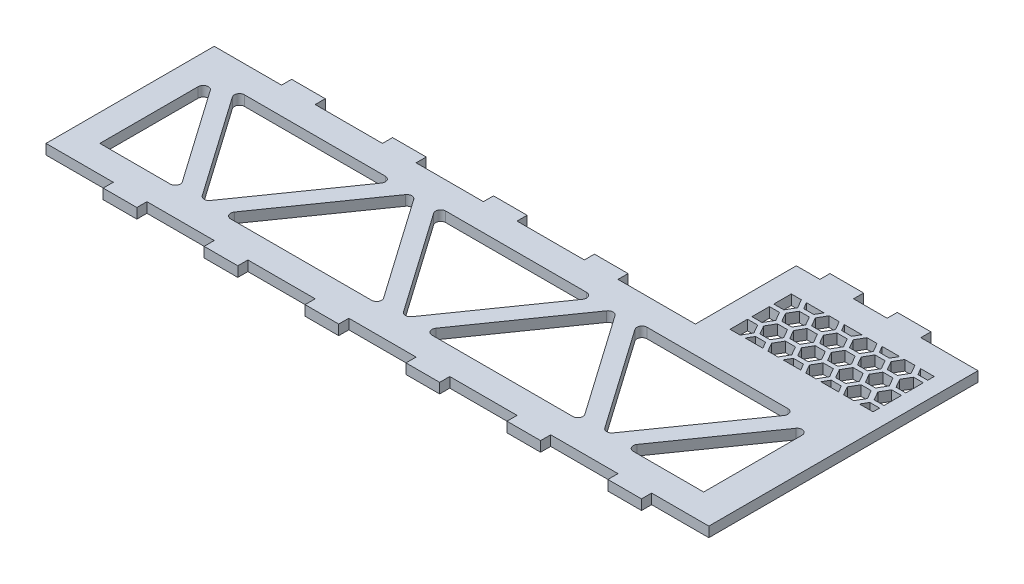
SolidWorks part; units mm, degrees
ref_plane "Front Plane" through (0, 0, 0) normal (0, 0, 1) x (1, 0, 0)
ref_plane "Top Plane" through (0, 0, 0) normal (0, 1, 0) x (1, 0, 0)
ref_plane "Right Plane" through (0, 0, 0) normal (1, 0, 0) x (0, 0, -1)
sketch "Sketch1" plane through (0, 0, 0) normal (0, 1, 0) x (1, 0, 0)
  line L0 (-71.5, -25) -> (125.5, -25)
  line L1 (-71.5, 25) -> (71.5, 25)
  line L2 (-71.5, 25) -> (-71.5, -25)
  line L8 (71.5, 25) -> (71.5, 55)
  line L9 (71.5, 55) -> (125.5, 55)
  line L10 (125.5, -25) -> (125.5, 55)
  point P0 (0, 0)
  dimension "D1" = 143
  dimension "D2" = 50
  dimension "D3" = 54
  dimension "D4" = 80
extrude "Boss-Extrude1" add sketch "Sketch1" along normal blind 3
sketch "Sketch6" plane through (0, 3, 0) normal (0, 1, 0) x (1, 0, 0)
  line L0 (-63.5, 12.2426) -> (-63.5, -17)
  line L1 (-63.5, -17) -> (-42.5744, -17)
  line L2 (-41.3457, -14.6396) -> (-60.7713, 13.103)
  line L3 (71.5, 25) -> (-71.5, 25) construction
  line L4 (-71.5, -25) -> (125.5, -25) construction
  line L5 (-71.5, 25) -> (-71.5, -25) construction
  line L6 (-55.7434, 14.6396) -> (-34.8178, -15.2452)
  line L7 (-32.3603, -15.2452) -> (-11.4348, 14.6396)
  line L8 (-12.6635, 17) -> (-54.5147, 17)
  line L9 (-4.9069, 15.2452) -> (-25.8325, -14.6396)
  line L10 (-2.4494, 15.2452) -> (18.4762, -14.6396)
  line L11 (17.2474, -17) -> (-24.6037, -17)
  line L12 (47.1584, 17) -> (5.3072, 17)
  line L13 (4.0785, 14.6396) -> (25.0041, -15.2452)
  line L14 (27.4615, -15.2452) -> (48.3871, 14.6396)
  line L15 (33.9894, -14.6396) -> (54.915, 15.2452)
  line L17 (77.0693, -17) -> (35.2181, -17)
  line L18 (78.298, -14.6396) -> (57.3724, 15.2452)
  line L19 (106.9802, 17) -> (65.1291, 17)
  line L20 (63.9003, 14.6396) -> (84.8259, -15.2452)
  line L21 (87.2834, -15.2452) -> (108.209, 14.6396)
  line L24 (95.04, -17) -> (115.9656, -17)
  line L25 (93.8113, -14.6396) -> (113.2368, 13.103)
  line L26 (115.9656, 12.2426) -> (115.9656, -17)
  arc A0 (95.04, -17) -> (93.8113, -14.6396) centre (95.04, -15.5) cw
  arc A1 (115.9656, 12.2426) -> (113.2368, 13.103) centre (114.4656, 12.2426) ccw
  arc A2 (77.0693, -17) -> (78.298, -14.6396) centre (77.0693, -15.5) ccw
  arc A3 (33.9894, -14.6396) -> (35.2181, -17) centre (35.2181, -15.5) ccw
  arc A4 (54.915, 15.2452) -> (57.3724, 15.2452) centre (56.1437, 14.3848) cw
  arc A5 (47.1584, 17) -> (48.3871, 14.6396) centre (47.1584, 15.5) cw
  arc A6 (25.0041, -15.2452) -> (27.4615, -15.2452) centre (26.2328, -14.3848) ccw
  arc A7 (5.3072, 17) -> (4.0785, 14.6396) centre (5.3072, 15.5) ccw
  arc A8 (18.4762, -14.6396) -> (17.2474, -17) centre (17.2474, -15.5) cw
  arc A9 (-4.9069, 15.2452) -> (-2.4494, 15.2452) centre (-3.6781, 14.3848) cw
  arc A10 (-25.8325, -14.6396) -> (-24.6037, -17) centre (-24.6037, -15.5) ccw
  arc A11 (-34.8178, -15.2452) -> (-32.3603, -15.2452) centre (-33.5891, -14.3848) ccw
  arc A12 (-11.4348, 14.6396) -> (-12.6635, 17) centre (-12.6635, 15.5) ccw
  arc A13 (-55.7434, 14.6396) -> (-54.5147, 17) centre (-54.5147, 15.5) cw
  arc A14 (-42.5744, -17) -> (-41.3457, -14.6396) centre (-42.5744, -15.5) ccw
  arc A15 (-63.5, 12.2426) -> (-60.7713, 13.103) centre (-62, 12.2426) cw
  arc A16 (87.2834, -15.2452) -> (84.8259, -15.2452) centre (86.0546, -14.3848) cw
  arc A17 (106.9802, 17) -> (108.209, 14.6396) centre (106.9802, 15.5) cw
  arc A18 (65.1291, 17) -> (63.9003, 14.6396) centre (65.1291, 15.5) ccw
  point P31 (92.1585, -17)
  point P34 (115.9656, 17)
  point P37 (79.9508, -17)
  point P40 (32.3367, -17)
  point P43 (56.1437, 17)
  point P46 (50.0398, 17)
  point P55 (-3.6781, 17)
  point P58 (-27.4852, -17)
  point P61 (-33.5891, -17)
  point P68 (-39.6929, -17)
  point P71 (-63.5, 17)
  dimension "D17" = 1.5
  dimension "D18" = 1.5
  dimension "D1" = 8
  dimension "D2" = 8
  dimension "D3" = 8
  dimension "D4" = 55
  dimension "D5" = 5
  dimension "D6" = 55
  dimension "D7" = 8
  dimension "D8" = 5
  dimension "D9" = 8
  dimension "D10" = 8
  dimension "D12" = 5
  dimension "D13" = 5
  dimension "D14" = 8
  dimension "D16" = 5
  dimension "D11" = 2
  dimension "D15" = 2
extrude "Cut-Extrude5" cut sketch "Sketch6" against normal blind 10
sketch "Sketch7" plane through (0, 3, 0) normal (0, 1, 0) x (1, 0, 0)
  line L0 (125.5, 55) -> (71.5, 55) construction
  line L1 (78, 47) -> (81, 47)
  line L4 (120.5, 47) -> (120.5, 45.0558)
  line L5 (89.2494, 28.8038) -> (92.2494, 28.8038)
  line L6 (100.4967, 28.8038) -> (103.4967, 28.8038)
  line L7 (104.9956, 28.8038) -> (110.245, 28.8038)
  line L9 (78, 47) -> (81, 47)
  line L10 (81, 47) -> (82.5, 44.4019)
  line L11 (82.5, 44.4019) -> (81, 41.8038)
  line L12 (81, 41.8038) -> (78, 41.8038)
  line L16 (78, 40.5) -> (81, 40.5)
  line L17 (81, 40.5) -> (82.5, 37.9019)
  line L18 (82.5, 37.9019) -> (81, 35.3038)
  line L19 (81, 35.3038) -> (78, 35.3038)
  line L22 (78, 34) -> (81, 34)
  line L23 (81, 34) -> (82.5, 31.4019)
  line L24 (82.5, 31.4019) -> (81, 28.8038)
  line L25 (81, 28.8038) -> (78, 28.8038)
  line L68 (82.1258, 41.1538) -> (83.6258, 43.7519)
  line L69 (82.1258, 41.1538) -> (83.6258, 38.5558)
  line L70 (83.6258, 43.7519) -> (86.6258, 43.7519)
  line L71 (83.6258, 38.5558) -> (86.6258, 38.5558)
  line L72 (82.5011, 28.8038) -> (87.7506, 28.8038)
  line L73 (88.1258, 41.1538) -> (86.6258, 38.5558)
  line L74 (88.1258, 41.1538) -> (86.6258, 43.7519)
  line L75 (88.1258, 34.6538) -> (86.6258, 32.0558)
  line L76 (83.6258, 32.0558) -> (86.6258, 32.0558)
  line L77 (82.1258, 34.6538) -> (83.6258, 32.0558)
  line L78 (82.1258, 34.6538) -> (83.6258, 37.2519)
  line L79 (83.6258, 37.2519) -> (86.6258, 37.2519)
  line L80 (88.1258, 34.6538) -> (86.6258, 37.2519)
  line L84 (82.5011, 28.8038) -> (83.6258, 30.7519)
  line L85 (83.6258, 30.7519) -> (86.6258, 30.7519)
  line L86 (87.7506, 28.8038) -> (86.6258, 30.7519)
  line L129 (82.1258, -17.3462) -> (83.6258, -19.9442) [skipped]
  line L130 (83.6258, -19.9442) -> (86.6258, -19.9442) [skipped]
  line L131 (88.1258, -17.3462) -> (86.6258, -19.9442) [skipped]
  line L133 (87.7483, 47) -> (86.6258, 45.0558)
  line L134 (83.6258, 45.0558) -> (86.6258, 45.0558)
  line L135 (82.5033, 47) -> (83.6258, 45.0558)
  line L139 (83.6258, 50.2519) -> (86.6258, 50.2519) [skipped]
  line L140 (82.1258, 47.6538) -> (83.6258, 50.2519) [skipped]
  line L141 (88.1258, 47.6538) -> (86.6258, 50.2519) [skipped]
  line L142 (89.2494, 47) -> (87.7494, 44.4019)
  line L143 (87.7494, 44.4019) -> (89.2494, 41.8038)
  line L144 (89.2494, 41.8038) -> (92.2494, 41.8038)
  line L145 (89.2494, 47) -> (92.2494, 47)
  line L146 (93.7494, 44.4019) -> (92.2494, 41.8038)
  line L147 (92.2494, 47) -> (93.7494, 44.4019)
  line L148 (89.2494, 40.5) -> (92.2494, 40.5)
  line L149 (92.2494, 40.5) -> (93.7494, 37.9019)
  line L150 (93.7494, 37.9019) -> (92.2494, 35.3038)
  line L151 (89.2494, 35.3038) -> (92.2494, 35.3038)
  line L152 (87.7494, 37.9019) -> (89.2494, 35.3038)
  line L153 (89.2494, 40.5) -> (87.7494, 37.9019)
  line L154 (89.2494, 34) -> (92.2494, 34)
  line L155 (92.2494, 34) -> (93.7494, 31.4019)
  line L156 (93.7494, 31.4019) -> (92.2494, 28.8038)
  line L157 (89.2494, 28.8038) -> (92.2494, 28.8038)
  line L158 (87.7494, 31.4019) -> (89.2494, 28.8038)
  line L159 (89.2494, 34) -> (87.7494, 31.4019)
  line L202 (111.7439, 28.8038) -> (114.7439, 28.8038)
  line L203 (82.5033, 47) -> (87.7483, 47)
  line L204 (98.9956, 47) -> (97.8731, 45.0558)
  line L205 (97.8731, 45.0558) -> (94.8731, 45.0558)
  line L206 (93.7506, 47) -> (94.8731, 45.0558)
  line L207 (98.9956, 47) -> (93.7506, 47)
  line L208 (93.3731, 41.1538) -> (94.8731, 43.7519)
  line L209 (97.8731, 43.7519) -> (94.8731, 43.7519)
  line L210 (99.3731, 41.1538) -> (97.8731, 43.7519)
  line L211 (99.3731, 41.1538) -> (97.8731, 38.5558)
  line L212 (97.8731, 38.5558) -> (94.8731, 38.5558)
  line L213 (93.3731, 41.1538) -> (94.8731, 38.5558)
  line L214 (93.3731, 34.6538) -> (94.8731, 37.2519)
  line L215 (97.8731, 37.2519) -> (94.8731, 37.2519)
  line L216 (99.3731, 34.6538) -> (97.8731, 37.2519)
  line L217 (99.3731, 34.6538) -> (97.8731, 32.0558)
  line L218 (97.8731, 32.0558) -> (94.8731, 32.0558)
  line L219 (93.3731, 34.6538) -> (94.8731, 32.0558)
  line L220 (93.7483, 28.8038) -> (94.8731, 30.7519)
  line L221 (97.8731, 30.7519) -> (94.8731, 30.7519)
  line L222 (98.9978, 28.8038) -> (97.8731, 30.7519)
  line L262 (93.7483, 28.8038) -> (98.9978, 28.8038)
  line L263 (103.4967, 47) -> (104.9967, 44.4019)
  line L264 (104.9967, 44.4019) -> (103.4967, 41.8038)
  line L265 (103.4967, 41.8038) -> (100.4967, 41.8038)
  line L266 (98.9967, 44.4019) -> (100.4967, 41.8038)
  line L267 (100.4967, 47) -> (98.9967, 44.4019)
  line L268 (103.4967, 47) -> (100.4967, 47)
  line L269 (103.4967, 40.5) -> (104.9967, 37.9019)
  line L270 (104.9967, 37.9019) -> (103.4967, 35.3038)
  line L271 (103.4967, 35.3038) -> (100.4967, 35.3038)
  line L272 (98.9967, 37.9019) -> (100.4967, 35.3038)
  line L273 (100.4967, 40.5) -> (98.9967, 37.9019)
  line L274 (103.4967, 40.5) -> (100.4967, 40.5)
  line L275 (103.4967, 34) -> (104.9967, 31.4019)
  line L276 (104.9967, 31.4019) -> (103.4967, 28.8038)
  line L277 (103.4967, 28.8038) -> (100.4967, 28.8038)
  line L278 (98.9967, 31.4019) -> (100.4967, 28.8038)
  line L279 (100.4967, 34) -> (98.9967, 31.4019)
  line L280 (103.4967, 34) -> (100.4967, 34)
  line L323 (116.458, 28.8038) -> (120.5, 28.8038)
  line L324 (104.9978, 47) -> (110.2428, 47)
  line L325 (110.2428, 47) -> (109.1203, 45.0558)
  line L326 (106.1203, 45.0558) -> (109.1203, 45.0558)
  line L327 (104.9978, 47) -> (106.1203, 45.0558)
  line L328 (110.6203, 41.1538) -> (109.1203, 38.5558)
  line L329 (106.1203, 38.5558) -> (109.1203, 38.5558)
  line L330 (104.6203, 41.1538) -> (106.1203, 38.5558)
  line L331 (104.6203, 41.1538) -> (106.1203, 43.7519)
  line L332 (106.1203, 43.7519) -> (109.1203, 43.7519)
  line L333 (110.6203, 41.1538) -> (109.1203, 43.7519)
  line L334 (110.6203, 34.6538) -> (109.1203, 32.0558)
  line L335 (106.1203, 32.0558) -> (109.1203, 32.0558)
  line L336 (104.6203, 34.6538) -> (106.1203, 32.0558)
  line L337 (104.6203, 34.6538) -> (106.1203, 37.2519)
  line L338 (106.1203, 37.2519) -> (109.1203, 37.2519)
  line L339 (110.6203, 34.6538) -> (109.1203, 37.2519)
  line L343 (104.9956, 28.8038) -> (106.1203, 30.7519)
  line L344 (106.1203, 30.7519) -> (109.1203, 30.7519)
  line L345 (110.245, 28.8038) -> (109.1203, 30.7519)
  line L382 (78, 47) -> (78, 41.8038)
  line L383 (111.7439, 47) -> (114.7439, 47)
  line L384 (114.7439, 47) -> (116.2439, 44.4019)
  line L385 (116.2439, 44.4019) -> (114.7439, 41.8038)
  line L386 (111.7439, 41.8038) -> (114.7439, 41.8038)
  line L387 (110.2439, 44.4019) -> (111.7439, 41.8038)
  line L388 (111.7439, 47) -> (110.2439, 44.4019)
  line L389 (111.7439, 40.5) -> (114.7439, 40.5)
  line L390 (114.7439, 40.5) -> (116.2439, 37.9019)
  line L391 (116.2439, 37.9019) -> (114.7439, 35.3038)
  line L392 (111.7439, 35.3038) -> (114.7439, 35.3038)
  line L393 (110.2439, 37.9019) -> (111.7439, 35.3038)
  line L394 (111.7439, 40.5) -> (110.2439, 37.9019)
  line L395 (111.7439, 34) -> (114.7439, 34)
  line L396 (114.7439, 34) -> (116.2439, 31.4019)
  line L397 (116.2439, 31.4019) -> (114.7439, 28.8038)
  line L398 (111.7439, 28.8038) -> (114.7439, 28.8038)
  line L399 (110.2439, 31.4019) -> (111.7439, 28.8038)
  line L400 (111.7439, 34) -> (110.2439, 31.4019)
  line L443 (78, 34) -> (78, 28.8038)
  line L445 (120.5, 45.0558) -> (117.5827, 45.0558)
  line L446 (116.4602, 47) -> (117.5827, 45.0558)
  line L447 (120.5, 47) -> (116.4602, 47)
  line L448 (116.0827, 41.1538) -> (117.5827, 43.7519)
  line L449 (120.5, 43.7519) -> (117.5827, 43.7519)
  line L452 (120.5, 38.5558) -> (117.5827, 38.5558)
  line L453 (116.0827, 41.1538) -> (117.5827, 38.5558)
  line L454 (116.0827, 34.6538) -> (117.5827, 37.2519)
  line L455 (120.5, 37.2519) -> (117.5827, 37.2519)
  line L458 (120.5, 32.0558) -> (117.5827, 32.0558)
  line L459 (116.0827, 34.6538) -> (117.5827, 32.0558)
  line L460 (116.458, 28.8038) -> (117.5827, 30.7519)
  line L461 (120.5, 30.7519) -> (117.5827, 30.7519)
  line L502 (78, 40.5) -> (78, 35.3038)
  line L526 (120.5, 30.7519) -> (120.5, 28.8038)
  line L527 (120.5, 37.2519) -> (120.5, 32.0558)
  line L528 (120.5, 43.7519) -> (120.5, 38.5558)
  line L529 (116.4602, 47) -> (120.5, 47)
  line L530 (111.7439, 47) -> (114.7439, 47)
  line L531 (104.9978, 47) -> (110.2428, 47)
  line L532 (100.4967, 47) -> (103.4967, 47)
  line L533 (93.7506, 47) -> (98.9956, 47)
  line L534 (89.2494, 47) -> (92.2494, 47)
  line L535 (82.5033, 47) -> (87.7483, 47)
  line L536 (81, 27.5) -> (82.5, 24.9019) [skipped]
  line L537 (82.1258, 28.1538) -> (83.6258, 25.5558) [skipped]
  line L538 (88.1258, 28.1538) -> (86.6258, 25.5558) [skipped]
  line L539 (89.2494, 27.5) -> (87.7494, 24.9019) [skipped]
  line L540 (92.2494, 27.5) -> (93.7494, 24.9019) [skipped]
  line L541 (100.4967, 27.5) -> (98.9967, 24.9019) [skipped]
  line L542 (103.4967, 27.5) -> (104.9967, 24.9019) [skipped]
  line L543 (106.1203, 25.5558) -> (109.1203, 25.5558) [skipped]
  line L544 (110.2439, 24.9019) -> (111.7439, 22.3038) [skipped]
  line L545 (116.2439, 24.9019) -> (114.7439, 22.3038) [skipped]
  line L546 (114.7439, 21) -> (116.2439, 18.4019) [skipped]
  line L547 (110.2439, 18.4019) -> (111.7439, 15.8038) [skipped]
  line L548 (110.6203, 15.1538) -> (109.1203, 17.7519) [skipped]
  line L549 (104.6203, 15.1538) -> (106.1203, 12.5558) [skipped]
  line L550 (103.4967, 14.5) -> (100.4967, 14.5) [skipped]
  line L551 (100.4967, 14.5) -> (98.9967, 11.9019) [skipped]
  line L552 (99.3731, 15.1538) -> (97.8731, 12.5558) [skipped]
  line L553 (93.3731, 15.1538) -> (94.8731, 17.7519) [skipped]
  line L554 (93.7494, 18.4019) -> (92.2494, 15.8038) [skipped]
  line L555 (87.7494, 18.4019) -> (89.2494, 15.8038) [skipped]
  line L556 (83.6258, 19.0558) -> (86.6258, 19.0558) [skipped]
  line L557 (82.1258, 21.6538) -> (83.6258, 19.0558) [skipped]
  line L558 (81, 22.3038) -> (78, 22.3038) [skipped]
  line L560 (78, 27.5) -> (81, 27.5) [skipped]
  line L562 (82.1258, 21.6538) -> (83.6258, 24.2519) [skipped]
  line L563 (88.1258, 21.6538) -> (86.6258, 24.2519) [skipped]
  line L564 (87.7494, 24.9019) -> (89.2494, 22.3038) [skipped]
  line L565 (88.1258, 21.6538) -> (86.6258, 19.0558) [skipped]
  line L566 (83.6258, 25.5558) -> (86.6258, 25.5558) [skipped]
  line L567 (83.6258, 24.2519) -> (86.6258, 24.2519) [skipped]
  line L568 (82.5, 24.9019) -> (81, 22.3038) [skipped]
  line L569 (93.3731, 28.1538) -> (94.8731, 25.5558) [skipped]
  line L570 (99.3731, 28.1538) -> (97.8731, 25.5558) [skipped]
  line L571 (97.8731, 25.5558) -> (94.8731, 25.5558) [skipped]
  line L572 (103.4967, 27.5) -> (100.4967, 27.5) [skipped]
  line L573 (104.6203, 28.1538) -> (106.1203, 25.5558) [skipped]
  line L574 (110.6203, 28.1538) -> (109.1203, 25.5558) [skipped]
  line L575 (111.7439, 27.5) -> (110.2439, 24.9019) [skipped]
  line L576 (114.7439, 27.5) -> (116.2439, 24.9019) [skipped]
  line L577 (111.7439, 27.5) -> (114.7439, 27.5) [skipped]
  line L578 (116.0827, 28.1538) -> (117.5827, 25.5558) [skipped]
  line L579 (120.5, 25.5558) -> (117.5827, 25.5558) [skipped]
  line L580 (120.5, 24.2519) -> (117.5827, 24.2519) [skipped]
  line L581 (120.5, 19.0558) -> (117.5827, 19.0558) [skipped]
  line L582 (120.5, 17.7519) -> (117.5827, 17.7519) [skipped]
  line L583 (120.5, 12.5558) -> (117.5827, 12.5558) [skipped]
  line L584 (120.5, 11.2519) -> (117.5827, 11.2519) [skipped]
  line L585 (116.0827, 8.6538) -> (117.5827, 11.2519) [skipped]
  line L586 (116.0827, 15.1538) -> (117.5827, 12.5558) [skipped]
  line L587 (116.0827, 15.1538) -> (117.5827, 17.7519) [skipped]
  line L588 (116.2439, 18.4019) -> (114.7439, 15.8038) [skipped]
  line L589 (111.7439, 15.8038) -> (114.7439, 15.8038) [skipped]
  line L590 (111.7439, 14.5) -> (114.7439, 14.5) [skipped]
  line L591 (111.7439, 14.5) -> (110.2439, 11.9019) [skipped]
  line L592 (106.1203, 11.2519) -> (109.1203, 11.2519) [skipped]
  line L593 (104.6203, 8.6538) -> (106.1203, 11.2519) [skipped]
  line L594 (103.4967, 8) -> (100.4967, 8) [skipped]
  line L595 (98.9967, 5.4019) -> (100.4967, 2.8038) [skipped]
  line L596 (99.3731, 2.1538) -> (97.8731, 4.7519) [skipped]
  line L597 (93.3731, 2.1538) -> (94.8731, -0.4442) [skipped]
  line L598 (92.2494, 1.5) -> (93.7494, -1.0981) [skipped]
  line L599 (89.2494, 1.5) -> (92.2494, 1.5) [skipped]
  line L600 (89.2494, 2.8038) -> (92.2494, 2.8038) [skipped]
  line L601 (89.2494, 8) -> (87.7494, 5.4019) [skipped]
  line L602 (88.1258, 15.1538) -> (86.6258, 12.5558) [skipped]
  line L603 (82.1258, 15.1538) -> (83.6258, 17.7519) [skipped]
  line L604 (82.5, 18.4019) -> (81, 15.8038) [skipped]
  line L605 (81, 15.8038) -> (78, 15.8038) [skipped]
  line L609 (81, 2.8038) -> (78, 2.8038) [skipped]
  line L610 (82.5, 5.4019) -> (81, 2.8038) [skipped]
  line L611 (82.1258, 2.1538) -> (83.6258, 4.7519) [skipped]
  line L612 (83.6258, 4.7519) -> (86.6258, 4.7519) [skipped]
  line L613 (83.6258, 6.0558) -> (86.6258, 6.0558) [skipped]
  line L614 (88.1258, 8.6538) -> (86.6258, 6.0558) [skipped]
  line L615 (87.7494, 11.9019) -> (89.2494, 9.3038) [skipped]
  line L616 (92.2494, 14.5) -> (93.7494, 11.9019) [skipped]
  line L617 (93.3731, 15.1538) -> (94.8731, 12.5558) [skipped]
  line L618 (97.8731, 12.5558) -> (94.8731, 12.5558) [skipped]
  line L619 (97.8731, 11.2519) -> (94.8731, 11.2519) [skipped]
  line L620 (93.3731, 8.6538) -> (94.8731, 11.2519) [skipped]
  line L621 (93.7494, 11.9019) -> (92.2494, 9.3038) [skipped]
  line L622 (89.2494, 9.3038) -> (92.2494, 9.3038) [skipped]
  line L623 (82.1258, 8.6538) -> (83.6258, 6.0558) [skipped]
  line L624 (88.1258, 8.6538) -> (86.6258, 11.2519) [skipped]
  line L625 (92.2494, 8) -> (93.7494, 5.4019) [skipped]
  line L626 (93.3731, 8.6538) -> (94.8731, 6.0558) [skipped]
  line L627 (99.3731, 8.6538) -> (97.8731, 6.0558) [skipped]
  line L628 (110.6203, 8.6538) -> (109.1203, 11.2519) [skipped]
  line L629 (110.2439, 11.9019) -> (111.7439, 9.3038) [skipped]
  line L630 (114.7439, 14.5) -> (116.2439, 11.9019) [skipped]
  line L631 (110.6203, 15.1538) -> (109.1203, 12.5558) [skipped]
  line L632 (106.1203, 17.7519) -> (109.1203, 17.7519) [skipped]
  line L633 (104.9967, 18.4019) -> (103.4967, 15.8038) [skipped]
  line L634 (98.9967, 18.4019) -> (100.4967, 15.8038) [skipped]
  line L635 (92.2494, 21) -> (93.7494, 18.4019) [skipped]
  line L636 (89.2494, 21) -> (87.7494, 18.4019) [skipped]
  line L637 (93.3731, 21.6538) -> (94.8731, 19.0558) [skipped]
  line L638 (99.3731, 21.6538) -> (97.8731, 19.0558) [skipped]
  line L639 (104.6203, 21.6538) -> (106.1203, 24.2519) [skipped]
  line L640 (104.6203, 21.6538) -> (106.1203, 19.0558) [skipped]
  line L641 (103.4967, 21) -> (104.9967, 18.4019) [skipped]
  line L642 (106.1203, 24.2519) -> (109.1203, 24.2519) [skipped]
  line L643 (104.9967, 24.9019) -> (103.4967, 22.3038) [skipped]
  line L644 (98.9967, 24.9019) -> (100.4967, 22.3038) [skipped]
  line L645 (99.3731, 21.6538) -> (97.8731, 24.2519) [skipped]
  line L646 (93.3731, 21.6538) -> (94.8731, 24.2519) [skipped]
  line L647 (93.7494, 24.9019) -> (92.2494, 22.3038) [skipped]
  line L648 (78, 21) -> (81, 21) [skipped]
  line L649 (88.1258, 15.1538) -> (86.6258, 17.7519) [skipped]
  line L650 (82.1258, 15.1538) -> (83.6258, 12.5558) [skipped]
  line L651 (81, 14.5) -> (82.5, 11.9019) [skipped]
  line L652 (81, 9.3038) -> (78, 9.3038) [skipped]
  line L653 (78, 8) -> (81, 8) [skipped]
  line L654 (78, 14.5) -> (81, 14.5) [skipped]
  line L655 (81, 21) -> (82.5, 18.4019) [skipped]
  line L657 (81, 1.5) -> (82.5, -1.0981) [skipped]
  line L658 (82.1258, 2.1538) -> (83.6258, -0.4442) [skipped]
  line L659 (88.1258, 2.1538) -> (86.6258, 4.7519) [skipped]
  line L660 (93.7494, 5.4019) -> (92.2494, 2.8038) [skipped]
  line L661 (87.7494, 5.4019) -> (89.2494, 2.8038) [skipped]
  line L662 (97.8731, 6.0558) -> (94.8731, 6.0558) [skipped]
  line L663 (100.4967, 8) -> (98.9967, 5.4019) [skipped]
  line L664 (99.3731, 8.6538) -> (97.8731, 11.2519) [skipped]
  line L665 (103.4967, 8) -> (104.9967, 5.4019) [skipped]
  line L666 (106.1203, 12.5558) -> (109.1203, 12.5558) [skipped]
  line L667 (104.6203, 15.1538) -> (106.1203, 17.7519) [skipped]
  line L668 (99.3731, 15.1538) -> (97.8731, 17.7519) [skipped]
  line L669 (89.2494, 14.5) -> (92.2494, 14.5) [skipped]
  line L670 (89.2494, 14.5) -> (87.7494, 11.9019) [skipped]
  line L671 (97.8731, 17.7519) -> (94.8731, 17.7519) [skipped]
  line L672 (97.8731, 19.0558) -> (94.8731, 19.0558) [skipped]
  line L673 (100.4967, 21) -> (98.9967, 18.4019) [skipped]
  line L674 (83.6258, 17.7519) -> (86.6258, 17.7519) [skipped]
  line L675 (89.2494, 21) -> (92.2494, 21) [skipped]
  line L676 (89.2494, 15.8038) -> (92.2494, 15.8038) [skipped]
  line L677 (110.6203, 2.1538) -> (109.1203, -0.4442) [skipped]
  line L678 (111.7439, 8) -> (114.7439, 8) [skipped]
  line L679 (114.7439, 8) -> (116.2439, 5.4019) [skipped]
  line L680 (116.2439, 5.4019) -> (114.7439, 2.8038) [skipped]
  line L681 (103.4967, 1.5) -> (104.9967, -1.0981) [skipped]
  line L682 (103.4967, 1.5) -> (100.4967, 1.5) [skipped]
  line L683 (99.3731, 2.1538) -> (97.8731, -0.4442) [skipped]
  line L684 (103.4967, 2.8038) -> (100.4967, 2.8038) [skipped]
  line L687 (82.1258, -4.3462) -> (83.6258, -1.7481) [skipped]
  line L688 (82.1258, -4.3462) -> (83.6258, -6.9442) [skipped]
  line L689 (81, -5) -> (82.5, -7.5981) [skipped]
  line L690 (81, -10.1962) -> (78, -10.1962) [skipped]
  line L691 (78, -11.5) -> (81, -11.5) [skipped]
  line L693 (81, -3.6962) -> (78, -3.6962) [skipped]
  line L694 (81, -11.5) -> (82.5, -14.0981) [skipped]
  line L695 (82.1258, -10.8462) -> (83.6258, -13.4442) [skipped]
  line L696 (88.1258, -10.8462) -> (86.6258, -13.4442) [skipped]
  line L697 (89.2494, -11.5) -> (87.7494, -14.0981) [skipped]
  line L698 (89.2494, -11.5) -> (92.2494, -11.5) [skipped]
  line L699 (93.3731, -10.8462) -> (94.8731, -13.4442) [skipped]
  line L700 (99.3731, -10.8462) -> (97.8731, -8.2481) [skipped]
  line L701 (98.9967, -7.5981) -> (100.4967, -10.1962) [skipped]
  line L702 (104.9967, -7.5981) -> (103.4967, -10.1962) [skipped]
  line L703 (106.1203, -8.2481) -> (109.1203, -8.2481) [skipped]
  line L704 (110.6203, -10.8462) -> (109.1203, -8.2481) [skipped]
  line L705 (110.2439, -7.5981) -> (111.7439, -10.1962) [skipped]
  line L706 (114.7439, -5) -> (116.2439, -7.5981) [skipped]
  line L707 (116.0827, -4.3462) -> (117.5827, -6.9442) [skipped]
  line L708 (120.5, -1.7481) -> (117.5827, -1.7481) [skipped]
  line L709 (120.5, -0.4442) -> (117.5827, -0.4442) [skipped]
  line L710 (120.5, 4.7519) -> (117.5827, 4.7519) [skipped]
  line L711 (120.5, 6.0558) -> (117.5827, 6.0558) [skipped]
  line L712 (116.0827, 21.6538) -> (117.5827, 19.0558) [skipped]
  line L713 (116.458, 22.3038) -> (117.5827, 24.2519) [skipped]
  line L714 (111.7439, 22.3038) -> (114.7439, 22.3038) [skipped]
  line L715 (110.245, 22.3038) -> (114.7439, 22.3038) [skipped]
  line L716 (103.4967, 22.3038) -> (100.4967, 22.3038) [skipped]
  line L717 (103.4967, 21) -> (100.4967, 21) [skipped]
  line L718 (103.4967, 15.8038) -> (100.4967, 15.8038) [skipped]
  line L719 (103.4967, 9.3038) -> (100.4967, 9.3038) [skipped]
  line L720 (104.9967, 11.9019) -> (103.4967, 9.3038) [skipped]
  line L721 (98.9967, -1.0981) -> (100.4967, -3.6962) [skipped]
  line L722 (99.3731, -4.3462) -> (97.8731, -1.7481) [skipped]
  line L723 (104.6203, 8.6538) -> (106.1203, 6.0558) [skipped]
  line L724 (97.8731, 4.7519) -> (94.8731, 4.7519) [skipped]
  line L725 (87.7494, -1.0981) -> (89.2494, -3.6962) [skipped]
  line L726 (88.1258, -4.3462) -> (86.6258, -1.7481) [skipped]
  line L727 (83.6258, -6.9442) -> (86.6258, -6.9442) [skipped]
  line L728 (83.6258, -8.2481) -> (86.6258, -8.2481) [skipped]
  line L729 (81, -16.6962) -> (78, -16.6962) [skipped]
  line L730 (89.2494, -16.6962) -> (92.2494, -16.6962) [skipped]
  line L731 (93.7494, -14.0981) -> (92.2494, -16.6962) [skipped]
  line L732 (98.9967, -14.0981) -> (100.4967, -16.6962) [skipped]
  line L733 (103.4967, -11.5) -> (104.9967, -14.0981) [skipped]
  line L734 (104.6203, -10.8462) -> (106.1203, -13.4442) [skipped]
  line L735 (110.6203, -10.8462) -> (109.1203, -13.4442) [skipped]
  line L736 (111.7439, -11.5) -> (114.7439, -11.5) [skipped]
  line L737 (111.7439, -11.5) -> (110.2439, -14.0981) [skipped]
  line L738 (114.7439, -11.5) -> (116.2439, -14.0981) [skipped]
  line L739 (116.0827, -10.8462) -> (117.5827, -13.4442) [skipped]
  line L740 (110.2439, -14.0981) -> (111.7439, -16.6962) [skipped]
  line L741 (116.2439, -14.0981) -> (114.7439, -16.6962) [skipped]
  line L742 (111.7439, -16.6962) -> (114.7439, -16.6962) [skipped]
  line L743 (104.9967, -14.0981) -> (103.4967, -16.6962) [skipped]
  line L744 (116.0827, -10.8462) -> (117.5827, -8.2481) [skipped]
  line L745 (100.4967, -11.5) -> (98.9967, -14.0981) [skipped]
  line L746 (87.7494, -14.0981) -> (89.2494, -16.6962) [skipped]
  line L747 (87.7506, -16.6962) -> (86.6258, -14.7481) [skipped]
  line L748 (82.5011, -16.6962) -> (83.6258, -14.7481) [skipped]
  line L749 (82.5, -14.0981) -> (81, -16.6962) [skipped]
  line L750 (83.6258, -14.7481) -> (86.6258, -14.7481) [skipped]
  line L751 (106.1203, -13.4442) -> (109.1203, -13.4442) [skipped]
  line L752 (99.3731, -10.8462) -> (97.8731, -13.4442) [skipped]
  line L753 (92.2494, -11.5) -> (93.7494, -14.0981) [skipped]
  line L754 (83.6258, -13.4442) -> (86.6258, -13.4442) [skipped]
  line L756 (116.2439, -7.5981) -> (114.7439, -10.1962) [skipped]
  line L757 (103.4967, -11.5) -> (100.4967, -11.5) [skipped]
  line L758 (97.8731, -13.4442) -> (94.8731, -13.4442) [skipped]
  line L759 (104.6203, -10.8462) -> (106.1203, -8.2481) [skipped]
  line L760 (93.3731, -10.8462) -> (94.8731, -8.2481) [skipped]
  line L761 (103.4967, -5) -> (104.9967, -7.5981) [skipped]
  line L762 (106.1203, -6.9442) -> (109.1203, -6.9442) [skipped]
  line L763 (104.6203, -4.3462) -> (106.1203, -6.9442) [skipped]
  line L764 (100.4967, -5) -> (98.9967, -7.5981) [skipped]
  line L765 (99.3731, -4.3462) -> (97.8731, -6.9442) [skipped]
  line L766 (93.3731, -4.3462) -> (94.8731, -6.9442) [skipped]
  line L767 (92.2494, -5) -> (93.7494, -7.5981) [skipped]
  line L768 (87.7494, -7.5981) -> (89.2494, -10.1962) [skipped]
  line L769 (88.1258, -10.8462) -> (86.6258, -8.2481) [skipped]
  line L770 (82.1258, -10.8462) -> (83.6258, -8.2481) [skipped]
  line L771 (93.7494, -7.5981) -> (92.2494, -10.1962) [skipped]
  line L772 (97.8731, -8.2481) -> (94.8731, -8.2481) [skipped]
  line L773 (89.2494, -5) -> (87.7494, -7.5981) [skipped]
  line L774 (110.6203, -4.3462) -> (109.1203, -6.9442) [skipped]
  line L775 (111.7439, -5) -> (110.2439, -7.5981) [skipped]
  line L776 (89.2494, -5) -> (92.2494, -5) [skipped]
  line L777 (88.1258, -4.3462) -> (86.6258, -6.9442) [skipped]
  line L780 (88.1258, 2.1538) -> (86.6258, -0.4442) [skipped]
  line L781 (89.2494, 1.5) -> (87.7494, -1.0981) [skipped]
  line L782 (93.3731, 2.1538) -> (94.8731, 4.7519) [skipped]
  line L784 (100.4967, 1.5) -> (98.9967, -1.0981) [skipped]
  line L785 (104.6203, 2.1538) -> (106.1203, -0.4442) [skipped]
  line L786 (111.7439, 1.5) -> (110.2439, -1.0981) [skipped]
  line L787 (104.9967, -1.0981) -> (103.4967, -3.6962) [skipped]
  line L788 (93.3731, -4.3462) -> (94.8731, -1.7481) [skipped]
  line L789 (103.4967, -3.6962) -> (100.4967, -3.6962) [skipped]
  line L790 (103.4967, -5) -> (100.4967, -5) [skipped]
  line L791 (104.6203, -4.3462) -> (106.1203, -1.7481) [skipped]
  line L792 (106.1203, -1.7481) -> (109.1203, -1.7481) [skipped]
  line L793 (111.7439, 1.5) -> (114.7439, 1.5) [skipped]
  line L794 (116.0827, 2.1538) -> (117.5827, 4.7519) [skipped]
  line L795 (116.0827, 2.1538) -> (117.5827, -0.4442) [skipped]
  line L796 (120.5, -6.9442) -> (117.5827, -6.9442) [skipped]
  line L797 (120.5, -8.2481) -> (117.5827, -8.2481) [skipped]
  line L798 (120.5, -13.4442) -> (117.5827, -13.4442) [skipped]
  line L799 (103.4967, -10.1962) -> (100.4967, -10.1962) [skipped]
  line L800 (103.4967, -16.6962) -> (100.4967, -16.6962) [skipped]
  line L801 (111.7439, -10.1962) -> (114.7439, -10.1962) [skipped]
  line L802 (111.7439, -5) -> (114.7439, -5) [skipped]
  line L803 (116.0827, 8.6538) -> (117.5827, 6.0558) [skipped]
  line L804 (114.7439, 1.5) -> (116.2439, -1.0981) [skipped]
  line L805 (111.7439, -3.6962) -> (114.7439, -3.6962) [skipped]
  line L806 (110.6203, -4.3462) -> (109.1203, -1.7481) [skipped]
  line L807 (110.6203, 2.1538) -> (109.1203, 4.7519) [skipped]
  line L808 (110.2439, 5.4019) -> (111.7439, 2.8038) [skipped]
  line L809 (111.7439, 8) -> (110.2439, 5.4019) [skipped]
  line L810 (110.2439, -1.0981) -> (111.7439, -3.6962) [skipped]
  line L811 (110.6203, 8.6538) -> (109.1203, 6.0558) [skipped]
  line L812 (111.7439, 2.8038) -> (114.7439, 2.8038) [skipped]
  line L813 (116.0827, -4.3462) -> (117.5827, -1.7481) [skipped]
  line L814 (111.7439, 9.3038) -> (114.7439, 9.3038) [skipped]
  line L815 (116.2439, 11.9019) -> (114.7439, 9.3038) [skipped]
  line L816 (116.2439, -1.0981) -> (114.7439, -3.6962) [skipped]
  line L817 (106.1203, -0.4442) -> (109.1203, -0.4442) [skipped]
  line L818 (106.1203, 4.7519) -> (109.1203, 4.7519) [skipped]
  line L819 (106.1203, 6.0558) -> (109.1203, 6.0558) [skipped]
  line L820 (104.6203, 2.1538) -> (106.1203, 4.7519) [skipped]
  line L821 (104.9967, 5.4019) -> (103.4967, 2.8038) [skipped]
  line L822 (103.4967, 14.5) -> (104.9967, 11.9019) [skipped]
  line L823 (106.1203, 19.0558) -> (109.1203, 19.0558) [skipped]
  line L824 (110.6203, 21.6538) -> (109.1203, 19.0558) [skipped]
  line L825 (98.9967, 11.9019) -> (100.4967, 9.3038) [skipped]
  line L826 (111.7439, 21) -> (114.7439, 21) [skipped]
  line L827 (111.7439, 21) -> (110.2439, 18.4019) [skipped]
  line L828 (110.245, 22.3038) -> (109.1203, 24.2519) [skipped]
  line L829 (97.8731, 24.2519) -> (94.8731, 24.2519) [skipped]
  line L830 (81, 8) -> (82.5, 5.4019) [skipped]
  line L831 (82.5, 11.9019) -> (81, 9.3038) [skipped]
  line L832 (82.1258, 8.6538) -> (83.6258, 11.2519) [skipped]
  line L833 (83.6258, 11.2519) -> (86.6258, 11.2519) [skipped]
  line L834 (83.6258, 12.5558) -> (86.6258, 12.5558) [skipped]
  line L835 (78, 1.5) -> (81, 1.5) [skipped]
  line L836 (83.6258, -0.4442) -> (86.6258, -0.4442) [skipped]
  line L837 (83.6258, -1.7481) -> (86.6258, -1.7481) [skipped]
  line L839 (78, -5) -> (81, -5) [skipped]
  line L840 (82.5, -1.0981) -> (81, -3.6962) [skipped]
  line L841 (82.5, -7.5981) -> (81, -10.1962) [skipped]
  line L842 (93.7494, -1.0981) -> (92.2494, -3.6962) [skipped]
  line L843 (89.2494, -3.6962) -> (92.2494, -3.6962) [skipped]
  line L844 (89.2494, -10.1962) -> (92.2494, -10.1962) [skipped]
  line L845 (89.2494, 8) -> (92.2494, 8) [skipped]
  line L846 (97.8731, -1.7481) -> (94.8731, -1.7481) [skipped]
  line L847 (97.8731, -0.4442) -> (94.8731, -0.4442) [skipped]
  line L848 (97.8731, -6.9442) -> (94.8731, -6.9442) [skipped]
  line L849 (89.2494, 27.5) -> (92.2494, 27.5) [skipped]
  dimension "D1" = 8
  dimension "D7" = 3
  dimension "D8" = 30
  dimension "D9" = 3
  dimension "D10" = 30
  dimension "D12" = 3
  dimension "D13" = 10
  dimension "D14" = 1.3
  dimension "D15" = 3
  dimension "D16" = 0.65
  dimension "D17" = 1.3019
  dimension "D18" = 3
  dimension "D19" = 3
  dimension "D22" = 1.3
  dimension "D23" = 1.2981
  dimension "D24" = 3
  dimension "D26" = 9
  dimension "D20" = 10
  dimension "D21" = 2
  dimension "D25" = 10
  dimension "D27" = 10
  dimension "D28" = 9
  dimension "D29" = 10
  dimension "D30" = 9
extrude "Cut-Extrude6" cut sketch "Sketch7" against normal blind 10
sketch "Sketch8" plane through (0, 0, 25) normal (0, 0, 1) x (1, 0, 0)
  line L0 (-51.5, 3) -> (-51.5, 0)
  line L1 (-71.5, 3) -> (125.5, 3) construction
  line L2 (-71.5, 0) -> (125.5, 0) construction
  line L3 (-51.5, 0) -> (-41.5, 0)
  line L4 (-41.5, 0) -> (-41.5, 3)
  line L5 (-41.5, 3) -> (-51.5, 3)
  line L6 (-71.5, 3) -> (-71.5, 0) construction
  line L35 (-11.5, 3) -> (-21.5, 3)
  line L36 (-21.5, 3) -> (-21.5, 0)
  line L37 (-21.5, 0) -> (-11.5, 0)
  line L38 (-11.5, 0) -> (-11.5, 3)
  line L39 (18.5, 3) -> (8.5, 3)
  line L40 (8.5, 3) -> (8.5, 0)
  line L41 (8.5, 0) -> (18.5, 0)
  line L42 (18.5, 0) -> (18.5, 3)
  line L43 (48.5, 3) -> (38.5, 3)
  line L44 (38.5, 3) -> (38.5, 0)
  line L45 (38.5, 0) -> (48.5, 0)
  line L46 (48.5, 0) -> (48.5, 3)
  line L47 (78.5, 3) -> (68.5, 3)
  line L48 (68.5, 3) -> (68.5, 0)
  line L49 (68.5, 0) -> (78.5, 0)
  line L50 (78.5, 0) -> (78.5, 3)
  line L51 (108.5, 3) -> (98.5, 3)
  line L52 (98.5, 3) -> (98.5, 0)
  line L53 (98.5, 0) -> (108.5, 0)
  line L54 (108.5, 0) -> (108.5, 3)
  dimension "D1" = 20
  dimension "D2" = 10
  dimension "D3" = 6
extrude "Boss-Extrude2" add sketch "Sketch8" along normal blind 3
sketch "Sketch10" plane through (0, 0, -25) normal (0, 0, -1) x (-1, 0, 0)
  line L0 (51.5, 0) -> (51.5, 3)
  line L1 (-71.5, 0) -> (71.5, 0) construction
  line L2 (-71.5, 3) -> (71.5, 3) construction
  line L3 (51.5, 3) -> (41.5, 3)
  line L4 (41.5, 3) -> (41.5, 0)
  line L5 (41.5, 0) -> (51.5, 0)
  line L6 (71.5, 3) -> (71.5, 0) construction
  line L7 (11.5, 0) -> (21.5, 0)
  line L8 (21.5, 0) -> (21.5, 3)
  line L9 (21.5, 3) -> (11.5, 3)
  line L10 (11.5, 3) -> (11.5, 0)
  line L11 (-18.5, 0) -> (-8.5, 0)
  line L12 (-8.5, 0) -> (-8.5, 3)
  line L13 (-8.5, 3) -> (-18.5, 3)
  line L14 (-18.5, 3) -> (-18.5, 0)
  line L15 (-48.5, 0) -> (-38.5, 0)
  line L16 (-38.5, 0) -> (-38.5, 3)
  line L17 (-38.5, 3) -> (-48.5, 3)
  line L18 (-48.5, 3) -> (-48.5, 0)
  dimension "D1" = 10
  dimension "D2" = 20
  dimension "D3" = 4
extrude "Boss-Extrude3" add sketch "Sketch10" along normal blind 3
sketch "Sketch11" plane through (0, 0, -55) normal (0, 0, -1) x (-1, 0, 0)
  line L0 (-125.5, 0) -> (-71.5, 0) construction
  line L1 (-78.5, 0) -> (-88.5, 0)
  line L2 (-78.5, 0) -> (-78.5, 3)
  line L3 (-78.5, 3) -> (-88.5, 3)
  line L4 (-88.5, 0) -> (-88.5, 3)
  line L5 (-125.5, 3) -> (-71.5, 3) construction
  line L6 (-71.5, 3) -> (-71.5, 0) construction
  line L7 (-98.5, 0) -> (-98.5, 3)
  line L8 (-98.5, 0) -> (-108.5, 0)
  line L9 (-108.5, 0) -> (-108.5, 3)
  line L10 (-98.5, 3) -> (-108.5, 3)
  dimension "D1" = 7
  dimension "D2" = 10
  dimension "D3" = 2
extrude "Boss-Extrude4" add sketch "Sketch11" along normal blind 3
